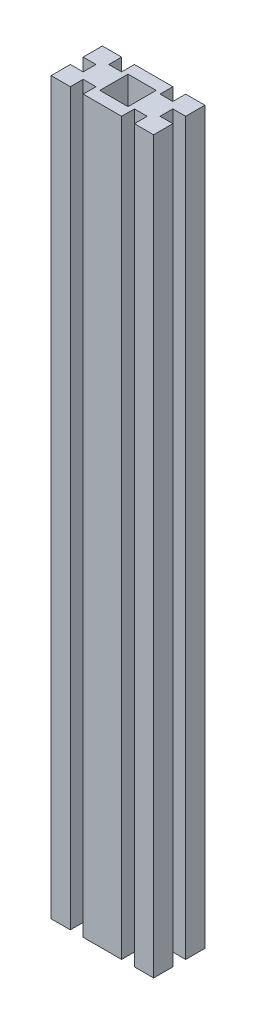
SolidWorks part; units mm, degrees
ref_plane "Front Plane" through (0, 0, 0) normal (0, 0, 1) x (1, 0, 0)
ref_plane "Top Plane" through (0, 0, 0) normal (0, 1, 0) x (1, 0, 0)
ref_plane "Right Plane" through (0, 0, 0) normal (1, 0, 0) x (0, 0, -1)
sketch "Sketch1" plane through (0, 0, 0) normal (0, 1, 0) x (1, 0, 0)
  line L1 (20, -10) -> (-20, -10)
  line L2 (20, -10) -> (20, 10)
  line L3 (20, 10) -> (-20, 10)
  line L4 (-20, -10) -> (-20, 10)
  line L5 (20, -10) -> (-20, 10) construction
  line L6 (20, 10) -> (-20, -10) construction
  point P0 (0, 0)
  dimension "D1" = 20
  dimension "D2" = 40
extrude "Body" add sketch "Sketch1" along normal blind 285
sketch "Sketch2" plane through (0, 285, 0) normal (0, 1, 0) x (1, 0, 0)
  line L0 (20, 10) -> (-20, 10) construction
  line L1 (-12.5, 10) -> (-7.5, 10)
  line L2 (-12.5, 10) -> (-12.5, 5)
  line L3 (-12.5, 5) -> (-7.5, 5)
  line L4 (-7.5, 10) -> (-7.5, 5)
  line L5 (-20, 10) -> (-20, -10) construction
  line L6 (-20, 2.5) -> (-15, 2.5)
  line L7 (-20, 2.5) -> (-20, -2.5)
  line L8 (-20, -2.5) -> (-15, -2.5)
  line L9 (-15, 2.5) -> (-15, -2.5)
  line L10 (-20, -10) -> (20, -10) construction
  line L11 (-12.5, -10) -> (-7.5, -10)
  line L12 (-12.5, -10) -> (-12.5, -5)
  line L13 (-12.5, -5) -> (-7.5, -5)
  line L14 (-7.5, -10) -> (-7.5, -5)
  line L15 (0, -1000) -> (0, 49000) construction
  line L16 (7.5, -10) -> (7.5, -5)
  line L17 (12.5, -5) -> (7.5, -5)
  line L18 (12.5, -10) -> (12.5, -5)
  line L19 (12.5, -10) -> (7.5, -10)
  line L20 (15, 2.5) -> (15, -2.5)
  line L21 (20, -2.5) -> (15, -2.5)
  line L22 (20, 2.5) -> (20, -2.5)
  line L23 (20, 2.5) -> (15, 2.5)
  line L24 (7.5, 10) -> (7.5, 5)
  line L25 (12.5, 5) -> (7.5, 5)
  line L26 (12.5, 10) -> (12.5, 5)
  line L27 (12.5, 10) -> (7.5, 10)
  line L29 (5.5, 5.5) -> (-5.5, 5.5)
  line L30 (5.5, 5.5) -> (5.5, -5.5)
  line L31 (5.5, -5.5) -> (-5.5, -5.5)
  line L32 (-5.5, 5.5) -> (-5.5, -5.5)
  line L33 (5.5, 5.5) -> (-5.5, -5.5) construction
  line L34 (5.5, -5.5) -> (-5.5, 5.5) construction
  point P18 (-15, 0)
  point P35 (0, 0)
  dimension "D1" = 5
  dimension "D2" = 5
  dimension "D3" = 7.5
  dimension "D4" = 11
extrude "Profilage" cut sketch "Sketch2" against normal through all
